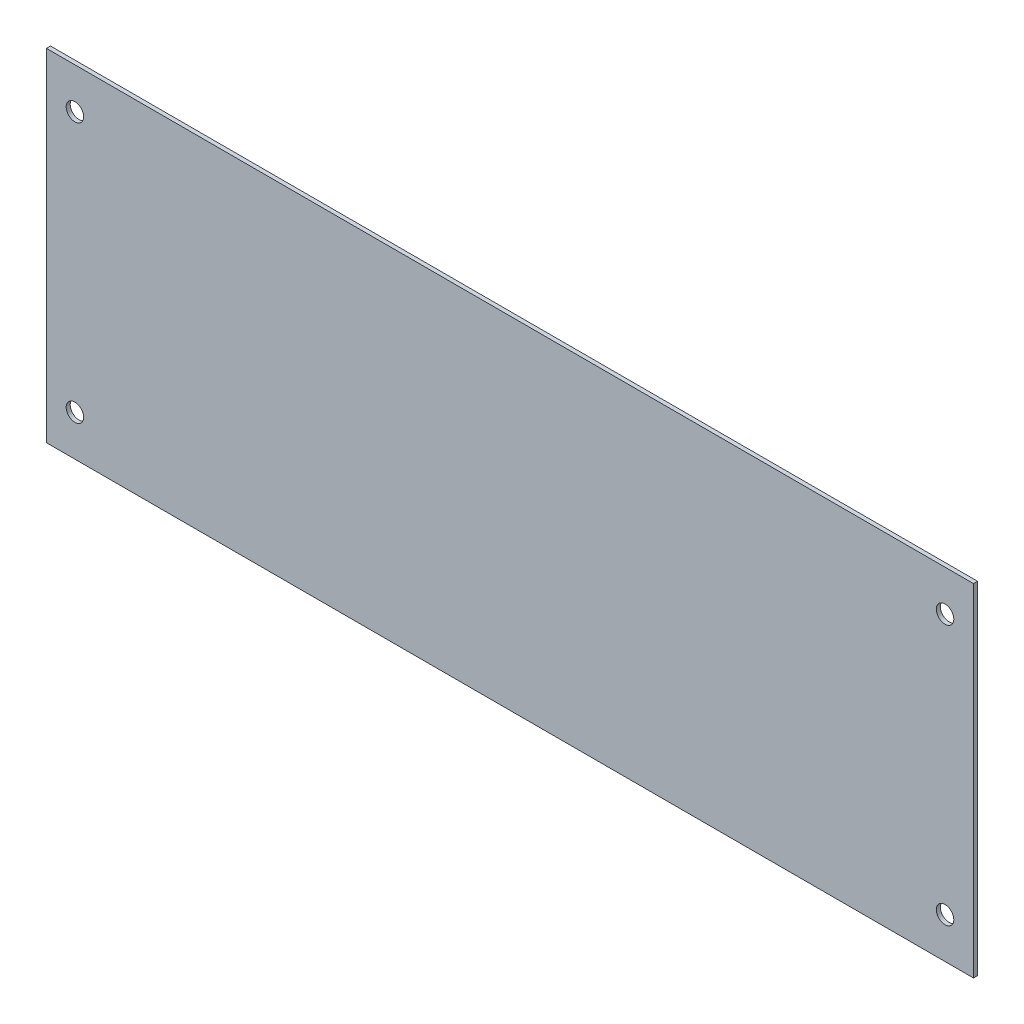
SolidWorks part; units mm, degrees
ref_plane "Спереди" through (0, 0, 0) normal (0, 0, 1) x (1, 0, 0)
ref_plane "Сверху" through (0, 0, 0) normal (0, 1, 0) x (1, 0, 0)
ref_plane "Справа" through (0, 0, 0) normal (1, 0, 0) x (0, 0, -1)
sketch "Эскиз1" plane through (0, 0, 0) normal (0, 0, 1) x (1, 0, 0)
  line L0 (0, 0) -> (58.1726, 0) construction
  line L1 (0, 0) -> (0, 47.3035) construction
  line L3 (-114, -42) -> (114, -42)
  line L4 (-114, -42) -> (-114, 42)
  line L5 (-114, 42) -> (114, 42)
  line L6 (114, -42) -> (114, 42)
  circle A8 centre (107, 32) radius 2.15
  circle A9 centre (-107, 32) radius 2.15
  circle A10 centre (-107, -32) radius 2.15
  circle A11 centre (107, -32) radius 2.15
  dimension "D14" = 4.3
  dimension "D15" = 10
  dimension "D16" = 7
  dimension "D3" = 64
  dimension "D1" = 84
  dimension "D2" = 228
extrude "Вытянуть1" add sketch "Эскиз1" along normal blind 1
